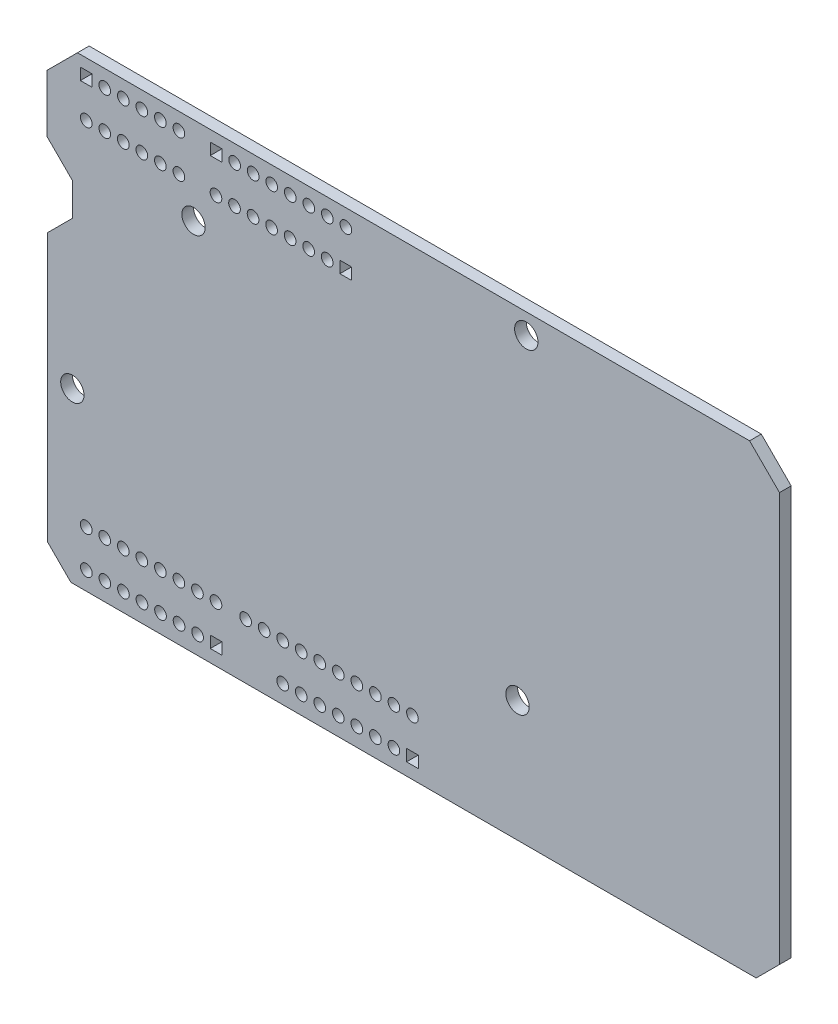
SolidWorks part; units mm, degrees
ref_plane "Plan de face" through (0, 0, 0) normal (0, 0, 1) x (1, 0, 0)
ref_plane "Plan de dessus" through (0, 0, 0) normal (0, 1, 0) x (1, 0, 0)
ref_plane "Plan de droite" through (0, 0, 0) normal (1, 0, 0) x (0, 0, -1)
sketch "Model" plane through (0, 0, 0) normal (0, 0, 1) x (1, 0, 0)
  line L804 (41.66, 55.06) -> (40.06, 55.06)
  line L805 (40.06, 55.06) -> (40.06, 56.66)
  line L806 (40.06, 56.66) -> (41.66, 56.66)
  line L807 (41.66, 56.66) -> (41.66, 55.06)
  line L1774 (4.5, 60.2) -> (4.5, 61.8)
  line L1775 (4.5, 61.8) -> (6.1, 61.8)
  line L1776 (6.1, 61.8) -> (6.1, 60.2)
  line L1777 (6.1, 60.2) -> (4.5, 60.2)
  line L1802 (50.8, 3.3) -> (50.8, 1.7)
  line L1803 (50.8, 1.7) -> (49.2, 1.7)
  line L1804 (49.2, 1.7) -> (49.2, 3.3)
  line L1805 (49.2, 3.3) -> (50.8, 3.3)
  line L1806 (23.9, 3.3) -> (23.9, 1.7)
  line L1807 (23.9, 1.7) -> (22.3, 1.7)
  line L1808 (22.3, 1.7) -> (22.3, 3.3)
  line L1809 (22.3, 3.3) -> (23.9, 3.3)
  line L1810 (22.3, 60.2) -> (22.3, 61.8)
  line L1811 (22.3, 61.8) -> (23.9, 61.8)
  line L1812 (23.9, 61.8) -> (23.9, 60.2)
  line L1813 (23.9, 60.2) -> (22.3, 60.2)
  line L1814 (0, 3.2) -> (0, 39.9)
  line L1815 (0, 39.9) -> (3.4, 43.3)
  line L1816 (3.4, 43.3) -> (3.4, 47.8)
  line L1817 (3.4, 47.8) -> (-0.1, 51.3)
  line L1818 (-0.1, 51.3) -> (-0.1, 59.1)
  line L1819 (-0.1, 59.1) -> (4.1, 63.3)
  line L1820 (4.1, 63.3) -> (96.2, 63.3)
  line L1821 (96.2, 63.3) -> (100.3, 59.2)
  line L1822 (100.3, 59.2) -> (100.3, 3.2)
  line L1823 (100.3, 3.2) -> (97.1, 0)
  line L1824 (97.1, 0) -> (3.2, 0)
  line L1825 (3.2, 0) -> (0, 3.2)
  circle A18 centre (5.3, 7.6) radius 0.8
  circle A19 centre (7.84, 7.6) radius 0.8
  circle A20 centre (10.38, 7.6) radius 0.8
  circle A21 centre (12.92, 7.6) radius 0.8
  circle A22 centre (15.46, 7.6) radius 0.8
  circle A23 centre (18, 7.6) radius 0.8
  circle A24 centre (20.54, 7.6) radius 0.8
  circle A25 centre (23.08, 7.6) radius 0.8
  circle A26 centre (27.14, 7.6) radius 0.8
  circle A27 centre (29.68, 7.6) radius 0.8
  circle A28 centre (32.22, 7.6) radius 0.8
  circle A29 centre (34.76, 7.6) radius 0.8
  circle A30 centre (37.3, 7.6) radius 0.8
  circle A31 centre (39.84, 7.6) radius 0.8
  circle A32 centre (42.38, 7.6) radius 0.8
  circle A33 centre (44.92, 7.6) radius 0.8
  circle A34 centre (47.46, 7.6) radius 0.8
  circle A35 centre (50, 7.6) radius 0.8
  circle A36 centre (38.32, 55.86) radius 0.8
  circle A37 centre (35.78, 55.86) radius 0.8
  circle A38 centre (33.24, 55.86) radius 0.8
  circle A39 centre (30.7, 55.86) radius 0.8
  circle A40 centre (28.16, 55.86) radius 0.8
  circle A41 centre (25.62, 55.86) radius 0.8
  circle A42 centre (23.08, 55.86) radius 0.8
  circle A43 centre (18, 55.86) radius 0.8
  circle A44 centre (15.46, 55.86) radius 0.8
  circle A45 centre (12.92, 55.86) radius 0.8
  circle A46 centre (10.38, 55.86) radius 0.8
  circle A47 centre (7.84, 55.86) radius 0.8
  circle A48 centre (5.3, 55.86) radius 0.8
  circle A57 centre (20, 51.3) radius 1.5999
  circle A58 centre (65.6, 60.5) radius 1.6
  circle A59 centre (64.4, 16.6) radius 1.6
  circle A60 centre (3.4, 23.1) radius 1.5999
  circle A68 centre (7.84, 61) radius 0.8
  circle A69 centre (10.38, 61) radius 0.8
  circle A70 centre (12.92, 61) radius 0.8
  circle A71 centre (15.46, 61) radius 0.8
  circle A72 centre (18, 61) radius 0.8
  circle A73 centre (47.46, 2.5) radius 0.8
  circle A74 centre (44.92, 2.5) radius 0.8
  circle A75 centre (42.38, 2.5) radius 0.8
  circle A76 centre (39.84, 2.5) radius 0.8
  circle A77 centre (37.3, 2.5) radius 0.8
  circle A78 centre (34.76, 2.5) radius 0.8
  circle A79 centre (32.22, 2.5) radius 0.8
  circle A80 centre (20.56, 2.5) radius 0.8
  circle A81 centre (18.02, 2.5) radius 0.8
  circle A82 centre (15.48, 2.5) radius 0.8
  circle A83 centre (12.94, 2.5) radius 0.8
  circle A84 centre (10.4, 2.5) radius 0.8
  circle A85 centre (7.86, 2.5) radius 0.8
  circle A86 centre (5.32, 2.5) radius 0.8
  circle A87 centre (25.64, 61) radius 0.8
  circle A88 centre (28.18, 61) radius 0.8
  circle A89 centre (30.72, 61) radius 0.8
  circle A90 centre (33.26, 61) radius 0.8
  circle A91 centre (35.8, 61) radius 0.8
  circle A92 centre (38.34, 61) radius 0.8
  circle A93 centre (40.88, 61) radius 0.8
extrude "Boss.-Extru.1" add sketch "Model" along normal blind 1.6
